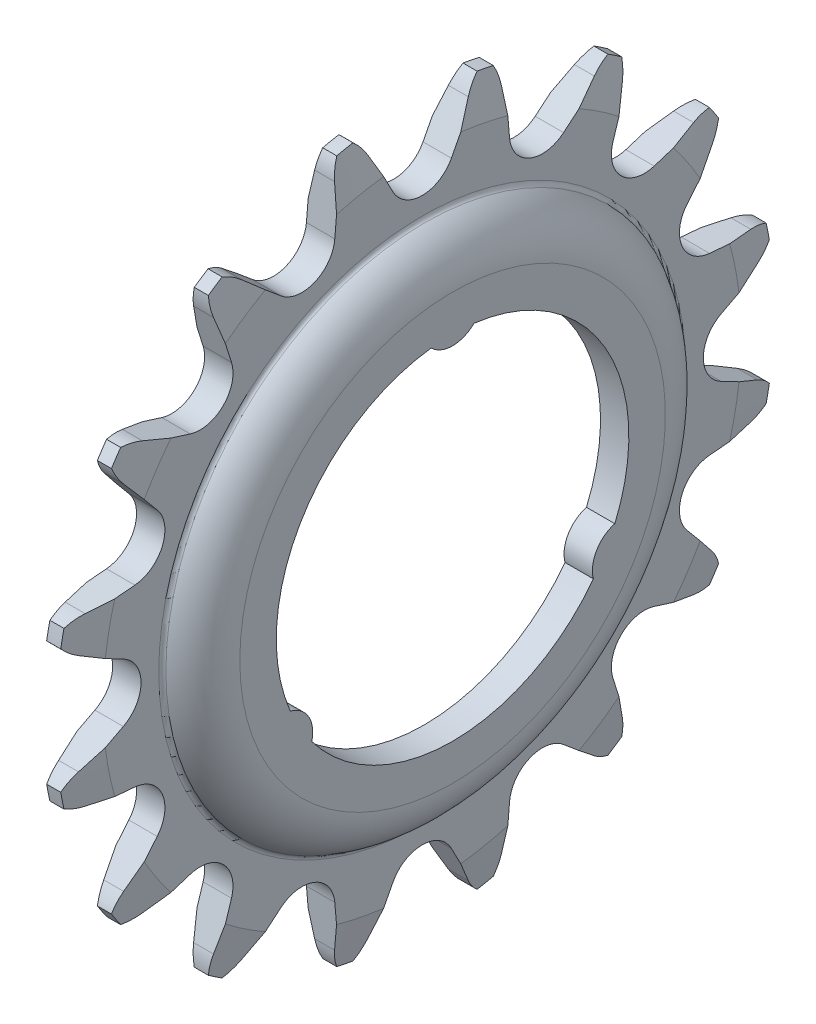
SolidWorks part; units mm, degrees
material "Stahl"
ref_plane "Ebene vorne" through (0, 0, 0) normal (0, 0, 1) x (1, 0, 0)
ref_plane "Ebene oben" through (0, 0, 0) normal (0, 1, 0) x (1, 0, 0)
ref_plane "Ebene rechts" through (0, 0, 0) normal (1, 0, 0) x (0, 0, -1)
sketch "Skizze1" plane through (0, 0, 0) normal (1, 0, 0) x (0, 0, -1)
  circle A0 centre (0, 0) radius 35.5
  circle A1 centre (0, 0) radius 26
  dimension "D1" = 71
  dimension "D2" = 52
extrude "Aufsatz-Linear austragen1" add sketch "Skizze1" along normal blind 2.8
chamfer "Fase1" distance 4 angle 10 2 edges at (0, 0, -35.5) (2.8, 0, -35.5)
sketch "Skizze2" plane through (2.8, 0, 0) normal (1, 0, 0) x (0, 0, -1)
  line L0 (0, 0) -> (0, 42) construction
  line L1 (-2.8828, 29.4993) -> (-4.9654, 33.5)
  line L2 (-4.1906, 38.901) -> (0, 42)
  line L4 (-8.0908, 36.0167) -> (-4.1906, 38.901)
  line L5 (4.1906, 38.901) -> (0, 42)
  line L6 (8.0908, 36.0167) -> (4.1906, 38.901)
  line L8 (2.8828, 29.4993) -> (4.9654, 33.5)
  arc A0 (-2.8828, 29.4993) -> (2.8828, 29.4993) centre (0, 31) ccw
  circle A2 centre (0, 0) radius 27.75 construction
  arc A3 (-8.0908, 36.0167) -> (-4.9654, 33.5) centre (-9.4005, 31.1913) cw
  arc A4 (4.9654, 33.5) -> (8.0908, 36.0167) centre (9.4005, 31.1913) cw
  dimension "D1" = 6.5
  dimension "D6" = 55.5
  dimension "D3" = 5
  dimension "D2" = 27.5
  dimension "D4" = 2.5
  dimension "D5" = 11
extrude "Schnitt-Linear austragen1" cut sketch "Skizze2" against normal through all both and the other way through all
pattern_circular "Kreismuster1" count 16 over 360 about axis through (0, 0, 0) along (1, 0, 0) of "Schnitt-Linear austragen1"
sketch "Skizze3" plane through (0, 0, 0) normal (0, 0, 1) x (1, 0, 0)
  line L0 (5.8, 17.4) -> (5.8, 21)
  line L1 (2.8, -31.5) -> (2.8, 31.5) construction
  line L2 (2.8, 26) -> (2.8, 27)
  line L3 (2.8, 27) -> (0, 27)
  line L4 (0, 27) -> (0, 26)
  line L5 (3, 22) -> (3, 17.4)
  line L6 (3, 17.4) -> (5.8, 17.4)
  line L7 (0, 22.8976) -> (0, 18.6703) construction
  line L8 (0, 0) -> (14.595, 0) construction
  arc A0 (2.8, 26) -> (3.0647, 25.5588) centre (3.3, 26) ccw
  arc A1 (3.0647, 25.5588) -> (5.8, 21) centre (0.6333, 21) cw
  arc A2 (0, 26) -> (2.64, 22.48) centre (3.6667, 26) ccw
  arc A3 (2.64, 22.48) -> (3, 22) centre (2.5, 22) cw
  dimension "D8" = 0.5
  dimension "D9" = 42
  dimension "D10" = 0.5
  dimension "D2" = 2.8
  dimension "D3" = 54
  dimension "D4" = 34.8
  dimension "D5" = 1
  dimension "D6" = 1
  dimension "D7" = 44
  dimension "D11" = 5.8
revolve "Rotation1" add sketch "Skizze3" angle 360 about L8
sketch "Skizze4" plane through (3, 0, 0) normal (-1, 0, 0) x (0, 0, 1)
  line L0 (-3, 19.4) -> (3, 19.4)
  line L1 (18.3009, -7.1019) -> (15.3009, -12.2981)
  line L2 (-15.3009, -12.2981) -> (-18.3009, -7.1019)
  arc A0 (-3, 19.4) -> (3, 19.4) centre (0, 19.4) ccw
  circle A2 centre (0, 0) radius 17.4 construction
  arc A3 (18.3009, -7.1019) -> (15.3009, -12.2981) centre (16.8009, -9.7) ccw
  arc A4 (-15.3009, -12.2981) -> (-18.3009, -7.1019) centre (-16.8009, -9.7) ccw
  point P14 (0, 0)
  dimension "D1" = 6
  dimension "D2" = 2
  dimension "D3" = 3
extrude "Aufsatz-Linear austragen2" add sketch "Skizze4" against normal up to surface (2.8 mm away) up to face at (5.8, 0, 21)
